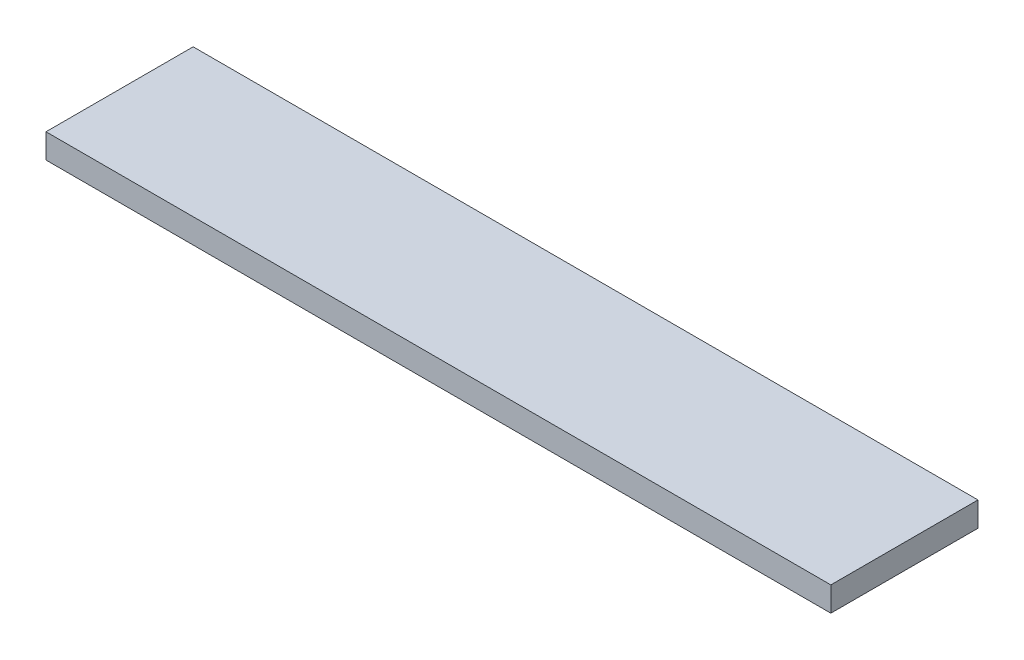
SolidWorks part; units mm, degrees
ref_plane "Front Plane" through (0, 0, 0) normal (0, 0, 1) x (1, 0, 0)
ref_plane "Top Plane" through (0, 0, 0) normal (0, 1, 0) x (1, 0, 0)
ref_plane "Right Plane" through (0, 0, 0) normal (1, 0, 0) x (0, 0, -1)
sketch "Sketch1" plane through (0, 0, 0) normal (0, 0, 1) x (1, 0, 0)
  line L1 (-203.2, 0) -> (203.2, 0)
  line L2 (-203.2, 0) -> (-203.2, -12.7)
  line L3 (-203.2, -12.7) -> (203.2, -12.7)
  line L4 (203.2, 0) -> (203.2, -12.7)
  dimension "D1" = 406.4
  dimension "D2" = 12.7
extrude "Boss-Extrude1" add sketch "Sketch1" along normal blind 76.2
